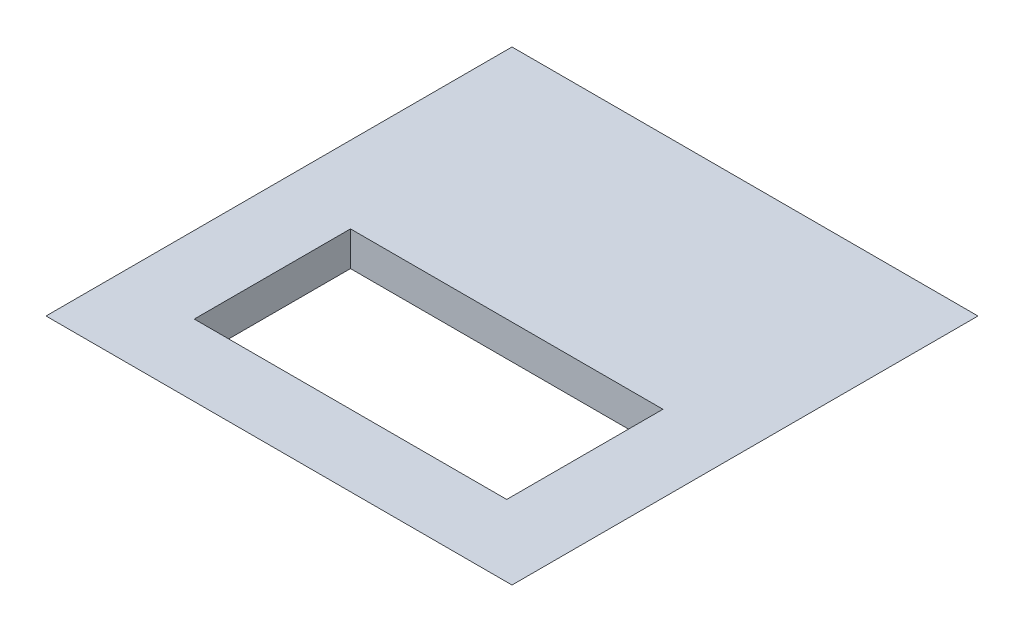
SolidWorks part; units mm, degrees
ref_plane "Front Plane" through (0, 0, 0) normal (0, 0, 1) x (1, 0, 0)
ref_plane "Top Plane" through (0, 0, 0) normal (0, 1, 0) x (1, 0, 0)
ref_plane "Right Plane" through (0, 0, 0) normal (1, 0, 0) x (0, 0, -1)
sketch "Sketch1" plane through (0, 0, 0) normal (0, 1, 0) x (1, 0, 0)
  line L1 (0, 0) -> (150, 0)
  line L2 (0, 0) -> (0, 150)
  line L3 (0, 150) -> (150, 150)
  line L4 (150, 0) -> (150, 150)
extrude "Boss-Extrude1" add sketch "Sketch1" along normal blind 13 draft 45 draft outward yes
sketch "Sketch2" plane through (0, 13, 0) normal (0, 1, 0) x (1, 0, 0)
  line L0 (-13, 75) -> (163, 75) construction
  line L1 (-13, 163) -> (-13, -13) construction
  line L2 (163, -13) -> (163, 163) construction
  line L3 (16.1123, 23.7215) -> (-13, 23.7215) construction
  line L4 (-13, -13) -> (163, -13) construction
  line L5 (75, 163) -> (75, -13) construction
  line L6 (163, 163) -> (-13, 163) construction
  line L7 (16, 73) -> (134, 73)
  line L8 (16, 73) -> (16, 14)
  line L9 (16, 14) -> (134, 14)
  line L10 (134, 73) -> (134, 14)
  line L11 (133.8877, 22.2798) -> (163, 22.2798) construction
  line L13 (27.0447, 14) -> (27.0447, -13) construction
extrude "Cut-Extrude1" cut sketch "Sketch2" against normal blind 13
